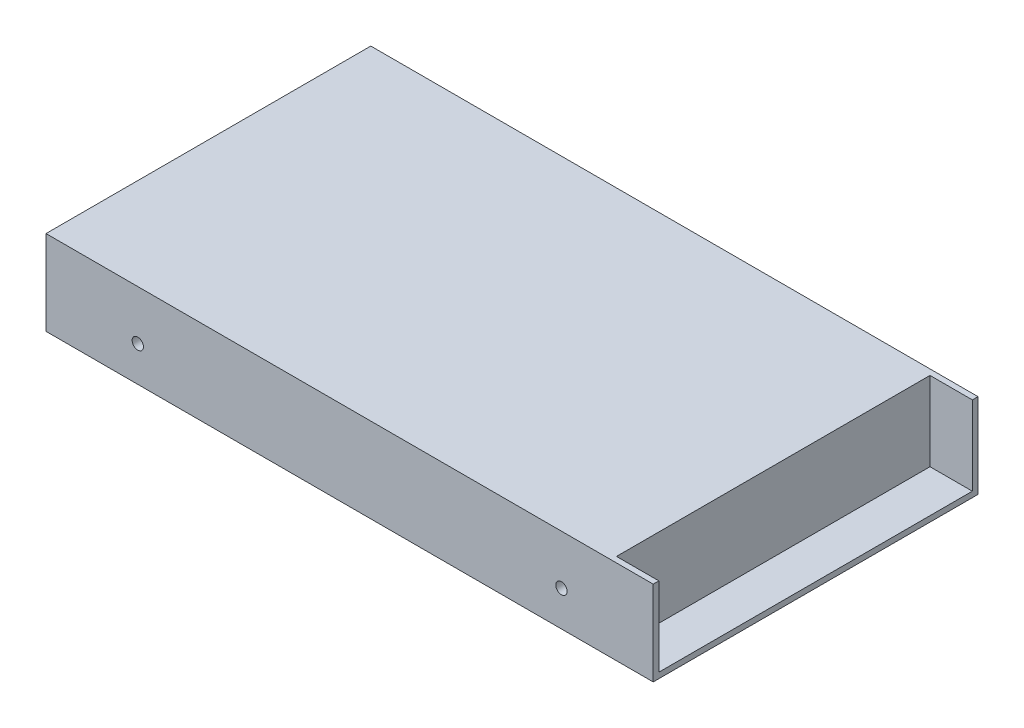
SolidWorks part; units mm, degrees
ref_plane "Front Plane" through (0, 0, 0) normal (0, 0, 1) x (1, 0, 0)
ref_plane "Top Plane" through (0, 0, 0) normal (0, 1, 0) x (1, 0, 0)
ref_plane "Right Plane" through (0, 0, 0) normal (1, 0, 0) x (0, 0, -1)
sketch "Sketch1" plane through (0, 0, 0) normal (0, 1, 0) x (1, 0, 0)
  line L1 (-107.5, -57.5) -> (107.5, -57.5)
  line L2 (-107.5, -57.5) -> (-107.5, 57.5)
  line L3 (-107.5, 57.5) -> (107.5, 57.5)
  line L4 (107.5, -57.5) -> (107.5, 57.5)
  line L5 (-107.5, -57.5) -> (107.5, 57.5) construction
  line L6 (-107.5, 57.5) -> (107.5, -57.5) construction
  point P0 (0, 0)
  dimension "D1" = 215
  dimension "D2" = 115
extrude "Boss-Extrude1" add sketch "Sketch1" along normal blind 30
sketch "Sketch2" plane through (0, 30, 0) normal (0, 1, 0) x (1, 0, 0)
  line L0 (107.5, -57.5) -> (107.5, 57.5) construction
  line L1 (107.5, 55.5) -> (92.5, 55.5)
  line L2 (107.5, 55.5) -> (107.5, -55.5)
  line L3 (107.5, -55.5) -> (92.5, -55.5)
  line L4 (92.5, 55.5) -> (92.5, -55.5)
  line L5 (107.5, 57.5) -> (-107.5, 57.5) construction
  line L6 (-107.5, -57.5) -> (107.5, -57.5) construction
  dimension "D1" = 15
  dimension "D2" = 2
  dimension "D3" = 2
extrude "Cut-Extrude1" cut sketch "Sketch2" against normal offset from surface (28 mm away) 2 up to face at (0, 0, 0)
sketch "Sketch3" plane through (0, 0, 57.5) normal (0, 0, 1) x (1, 0, 0)
  line L0 (107.5, 30) -> (107.5, 0) construction
  line L1 (-107.5, 0) -> (107.5, 0) construction
  circle A0 centre (75, 12.5) radius 2
  circle A1 centre (-75, 12.5) radius 2
  dimension "D1" = 32.5
  dimension "D3" = 4
  dimension "D4" = 150
  dimension "D2" = 12.5
extrude "Cut-Extrude2" cut sketch "Sketch3" against normal blind 5
sketch "Sketch4" plane through (0, 0, 0) normal (0, -1, 0) x (1, 0, 0)
  line L0 (107.5, 57.5) -> (107.5, -57.5) construction
  line L1 (107.5, -57.5) -> (-107.5, -57.5) construction
  circle A0 centre (75, -25) radius 2
  circle A1 centre (-75, -25) radius 2
  circle A2 centre (-75, 25) radius 2
  circle A3 centre (75, 25) radius 2
  dimension "D1" = 32.5
  dimension "D2" = 4
  dimension "D4" = 150
  dimension "D5" = 50
  dimension "D3" = 32.5
extrude "Cut-Extrude3" cut sketch "Sketch4" against normal blind 3
sketch "Sketch5" plane through (0, 0, -57.5) normal (0, 0, -1) x (-1, 0, 0)
  line L0 (-107.5, 30) -> (-107.5, 0) construction
  line L1 (-107.5, 0) -> (107.5, 0) construction
  circle A0 centre (-75, 12.5) radius 2
  circle A1 centre (75, 12.5) radius 2
  dimension "D1" = 32.5
  dimension "D3" = 150
  dimension "D4" = 4
  dimension "D2" = 12.5
extrude "Cut-Extrude4" cut sketch "Sketch5" against normal blind 5
